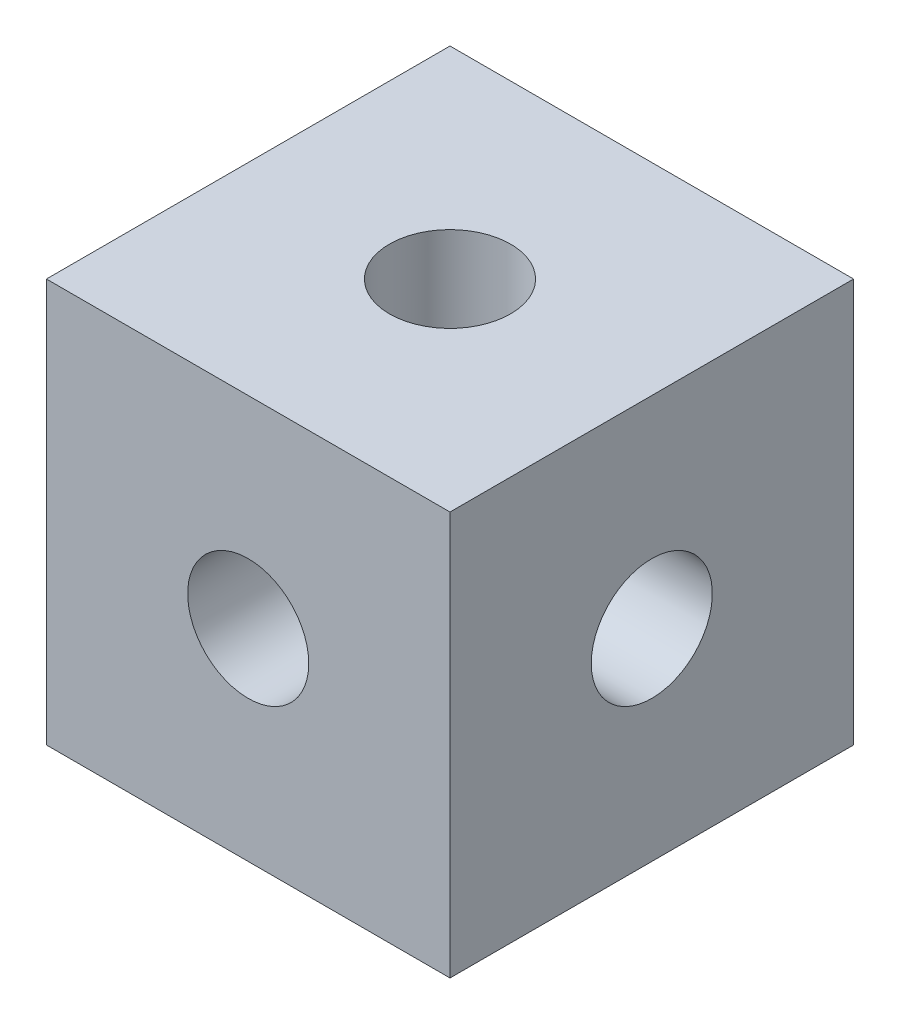
SolidWorks part; units mm, degrees
material "6061-T6 (SS)"
ref_plane "前视基准面" through (0, 0, 0) normal (0, 0, 1) x (1, 0, 0)
ref_plane "上视基准面" through (0, 0, 0) normal (0, 1, 0) x (1, 0, 0)
ref_plane "右视基准面" through (0, 0, 0) normal (1, 0, 0) x (0, 0, -1)
sketch "草图1" plane through (0, 0, 0) normal (0, 0, 1) x (1, 0, 0)
  line L1 (0, 0) -> (10, 0)
  line L2 (0, 0) -> (0, 10)
  line L3 (0, 10) -> (10, 10)
  line L4 (10, 0) -> (10, 10)
  dimension "D1" = 10
  dimension "D2" = 10
extrude "凸台-拉伸1" add sketch "草图1" along normal blind 10
sketch "草图2" plane through (0, 0, 10) normal (0, 0, 1) x (1, 0, 0)
  line L0 (10, 5) -> (-1.0149, 5) construction
  line L1 (10, 0) -> (10, 10) construction
  line L2 (5, 10) -> (5, -0.3396) construction
  line L3 (10, 10) -> (0, 10) construction
  circle A0 centre (5, 5) radius 1.5
  dimension "D1" = 3
extrude "切除-拉伸1" cut sketch "草图2" against normal through all
cosmetic thread "装饰螺纹线15" parameters "D2"=4
sketch "草图3" plane through (0, 0, 0) normal (-1, 0, 0) x (0, 0, 1)
  line L0 (0, 10) -> (0, 0) construction
  line L1 (10, 0) -> (0, 0) construction
  circle A0 centre (5, 5) radius 1.5
  dimension "D1" = 3
  dimension "D2" = 5
  dimension "D3" = 5
extrude "切除-拉伸2" cut sketch "草图3" against normal through all
cosmetic thread "装饰螺纹线12" parameters "D2"=4
cosmetic thread "装饰螺纹线16" parameters "D2"=4
sketch "草图4" plane through (0, 10, 0) normal (0, 1, 0) x (1, 0, 0)
  line L0 (0, -10) -> (0, 0) construction
  line L1 (10, 0) -> (0, 0) construction
  circle A0 centre (5, -5) radius 1.5
  dimension "D1" = 3
  dimension "D2" = 5
  dimension "D3" = 5
extrude "切除-拉伸3" cut sketch "草图4" against normal through all
cosmetic thread "装饰螺纹线13" parameters "D2"=4
cosmetic thread "装饰螺纹线14" parameters "D2"=4
